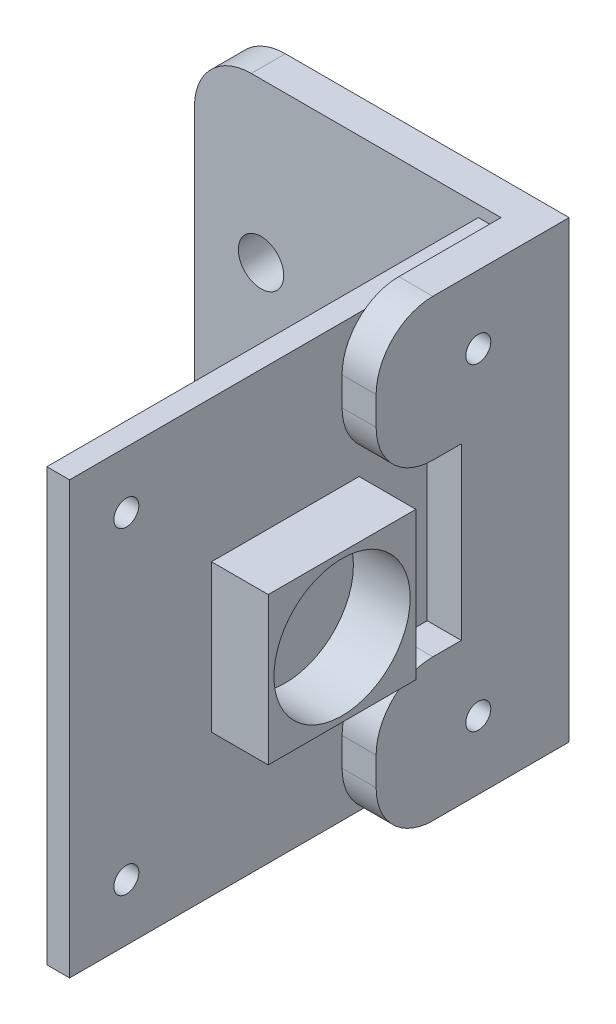
SolidWorks part; units mm, degrees
ref_plane "Front Plane" through (0, 0, 0) normal (1, 0, 0) x (0, 1, 0)
ref_plane "Top Plane" through (0, 0, 0) normal (0, 0, 1) x (0, 1, 0)
ref_plane "Right Plane" through (0, 0, 0) normal (0, 1, 0) x (-1, 0, 0)
sketch "Sketch1" plane through (0, 0, 0) normal (1, 0, 0) x (0, 1, 0)
  line L0 (0, 0) -> (-19, 0) construction
  line L1 (-19, -19) -> (19, -19)
  line L2 (-19, -19) -> (-19, 19)
  line L3 (-19, 19) -> (19, 19)
  line L4 (19, -19) -> (19, 19)
  line L5 (-19, -19) -> (19, 19) construction
  line L6 (-19, 19) -> (19, -19) construction
  line L7 (0, 0) -> (0, 19) construction
  circle A0 centre (-14, 14) radius 1.1
  circle A1 centre (-14, -14) radius 1.1
  circle A2 centre (14, -14) radius 1.1
  circle A3 centre (14, 14) radius 1.1
  point P0 (0, 0)
  dimension "D2" = 2.2
  dimension "D1" = 38
  dimension "D3" = 5
  dimension "D4" = 5
extrude "Boss-Extrude1" add sketch "Sketch1" along normal blind 2
sketch "Sketch2" plane through (2, 0, 0) normal (1, 0, 0) x (0, 1, 0)
  line L1 (-6.5, -6.5) -> (6.5, -6.5)
  line L2 (-6.5, -6.5) -> (-6.5, 6.5)
  line L3 (-6.5, 6.5) -> (6.5, 6.5)
  line L4 (6.5, -6.5) -> (6.5, 6.5)
  line L5 (-6.5, -6.5) -> (6.5, 6.5) construction
  line L6 (-6.5, 6.5) -> (6.5, -6.5) construction
  circle A0 centre (0, 0) radius 6.5
  circle A1 centre (0, 0) radius 6
  dimension "D1" = 13
  dimension "D2" = 12
  dimension "D3" = 13
extrude "Boss-Extrude2" add sketch "Sketch2" along normal blind 5 contours A0 L3 L2 | A0 L4 L3 | A0 A1 | A0 L1 L4 | A0 L2 L1
sketch "Sketch3" plane through (2, 0, 0) normal (1, 0, 0) x (0, 1, 0)
  line L0 (19, -19) -> (19, 19) construction
  line L1 (-20, -5) -> (20, -5)
  line L2 (-20, -5) -> (-20, -22)
  line L3 (-20, -22) -> (20, -22)
  line L4 (20, -5) -> (20, -22)
  line L5 (-19, 19) -> (-19, -19) construction
  line L6 (-19, -19) -> (19, -19) construction
  line L8 (7.5, -12.5) -> (-7.5, -12.5)
  line L9 (7.5, -12.5) -> (7.5, 2.5)
  line L10 (7.5, 2.5) -> (-7.5, 2.5)
  line L11 (-7.5, -12.5) -> (-7.5, 2.5)
  line L12 (7.5, -12.5) -> (-7.5, 2.5) construction
  line L13 (7.5, 2.5) -> (-7.5, -12.5) construction
  circle A0 centre (0, -5) radius 6.5
  circle A1 centre (0, -5) radius 6
  line M7 (19, -19) -> (19, 19)
  line M9 (-19, 19) -> (-19, -19)
  line M10 (-19, -19) -> (19, -19)
  circle M20 centre (14, -14) radius 1.1
  circle M21 centre (-14, -14) radius 1.1
  dimension "D1" = 13
  dimension "D2" = 1
  dimension "D6" = 12
  dimension "D3" = 1
  dimension "D4" = 3
  dimension "D5" = 5
  dimension "D7" = 15
extrude "Boss-Extrude3" add sketch "Sketch3" along normal blind 3 separate body contours L8 L11 L1 L9 M9 M10 M7 M21 M20 | L4 L1 L2 L3 M7 M10 M9 | A1
sketch "Sketch4" plane through (5, 0, 0) normal (1, 0, 0) x (0, 1, 0)
  line L0 (-20, -5) -> (-20, -22) construction
  line L1 (20, -22) -> (-20, -22)
  line L2 (20, -22) -> (20, -19)
  line L3 (20, -19) -> (-20, -19)
  line L4 (-20, -22) -> (-20, -19)
  dimension "D1" = 3
extrude "Boss-Extrude4" add sketch "Sketch4" against normal blind 30
sketch "Sketch5" plane through (0, 0, -19) normal (0, 0, 1) x (1, 0, 0)
  line L0 (-25, 20) -> (2, 20) construction
  circle A0 centre (-19.135, 6) radius 2
  circle A1 centre (-19.135, -6) radius 2
  dimension "D2" = 4
  dimension "D3" = 4
  dimension "D1" = 12
  dimension "D4" = 14
extrude "Cut-Extrude1" cut sketch "Sketch5" against normal blind 10
fillet "Fillet1" radius 5 6 edges at (-25, -20, -20.5) (-25, 20, -20.5) (3.5, -20, -5) (3.5, 20, -5) (3.5, 7.5, -5) (3.5, -7.5, -5)
equation "\"D3@Sketch5\"=\"D2@Sketch5\""
